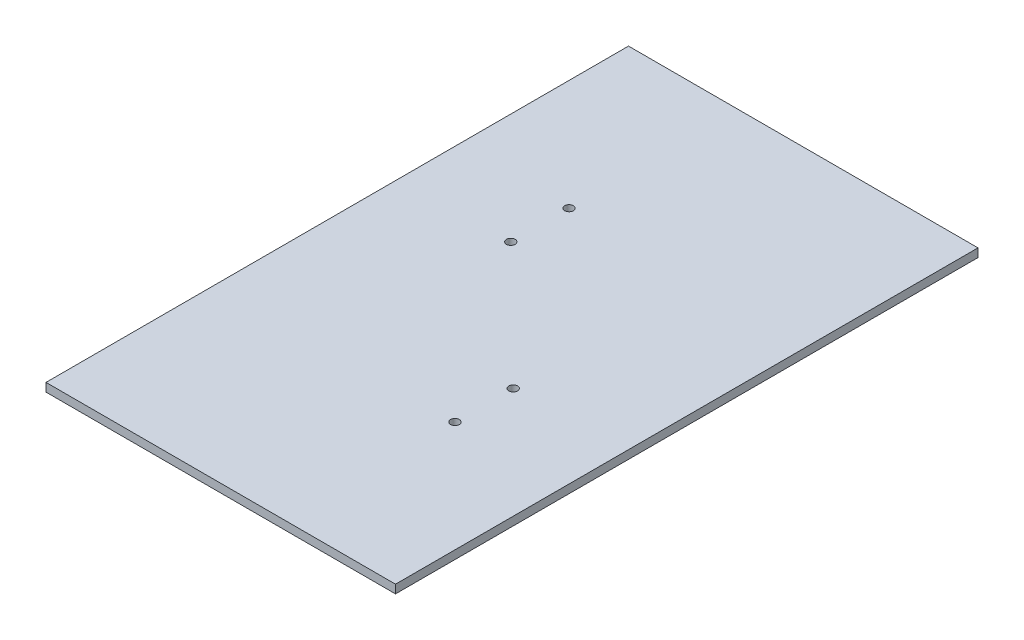
SolidWorks part; units mm, degrees
ref_plane "Front Plane" through (0, 0, 0) normal (0, 0, 1) x (1, 0, 0)
ref_plane "Top Plane" through (0, 0, 0) normal (0, 1, 0) x (1, 0, 0)
ref_plane "Right Plane" through (0, 0, 0) normal (1, 0, 0) x (0, 0, -1)
sketch "Sketch1" plane through (0, 0, 0) normal (0, 1, 0) x (1, 0, 0)
  line L0 (0, 100) -> (0, -100) construction
  line L1 (60, -100) -> (-60, -100)
  line L2 (60, -100) -> (60, 100)
  line L3 (60, 100) -> (-60, 100)
  line L4 (-60, -100) -> (-60, 100)
  line L5 (60, -100) -> (-60, 100) construction
  line L6 (60, 100) -> (-60, -100) construction
  line L7 (-60, 0) -> (60, 0) construction
  line L8 (-22, 41.5784) -> (-22, 21.5784) construction
  line L9 (22, 41.5784) -> (22, 21.5784) construction
  line L10 (22, -41.5784) -> (22, -21.5784) construction
  circle A0 centre (-22, 41.5784) radius 1.5
  circle A1 centre (-22, 21.5784) radius 1.5
  circle A2 centre (22, 21.5784) radius 1.5 construction
  circle A3 centre (22, 41.5784) radius 1.5 construction
  circle A4 centre (22, -21.5784) radius 1.5
  circle A5 centre (22, -41.5784) radius 1.5
  point P0 (0, 0)
  dimension "D3" = 3
  dimension "D4" = 20
  dimension "D1" = 120
  dimension "D2" = 200
  dimension "D5" = 44
extrude "Boss-Extrude1" add sketch "Sketch1" along normal mid plane 2.9
